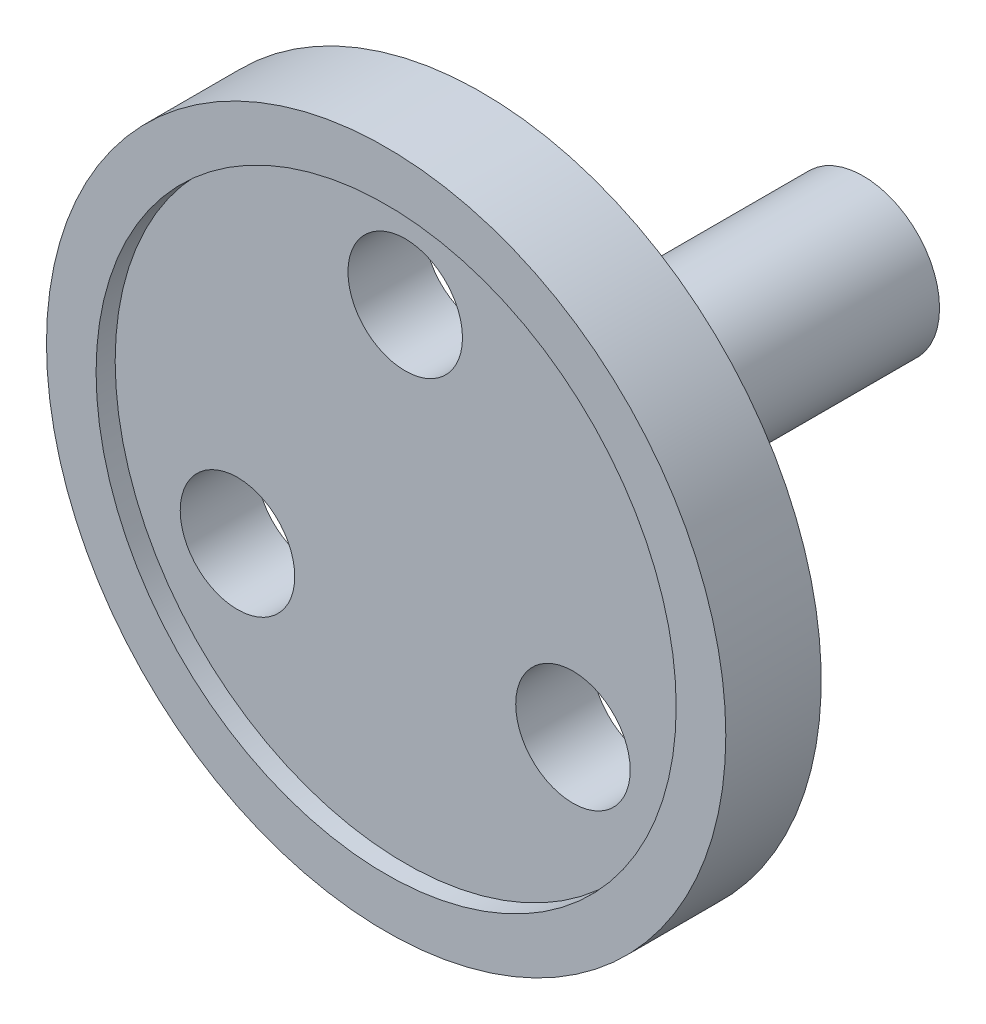
SolidWorks part; units mm, degrees
material "合金钢"
ref_plane "前视基准面" through (0, 0, 0) normal (0, 0, 1) x (1, 0, 0)
ref_plane "上视基准面" through (0, 0, 0) normal (0, 1, 0) x (1, 0, 0)
ref_plane "右视基准面" through (0, 0, 0) normal (1, 0, 0) x (0, 0, -1)
sketch "草图1" plane through (0, 0, 0) normal (0, 0, 1) x (1, 0, 0)
  circle A0 centre (0, 0) radius 8.9
  circle A1 centre (0, 0) radius 5.075 construction
  circle A2 centre (0, 5.075) radius 1.5
  circle A3 centre (4.3951, -2.5375) radius 1.5
  circle A4 centre (-4.3951, -2.5375) radius 1.5
  point P12 (0, 0)
  dimension "D1" = 3
extrude "凸台-拉伸1" add sketch "草图1" along normal blind 3.5
sketch "草图2" plane through (0, 0, 3.5) normal (0, 0, 1) x (1, 0, 0)
  circle A0 centre (0, 0) radius 7.6
extrude "切除-拉伸1" cut sketch "草图2" against normal blind 0.5
sketch "草图3" plane through (0, 0, 0) normal (0, 0, -1) x (-1, 0, 0)
  circle A0 centre (0, 0) radius 2
extrude "凸台-拉伸2" add sketch "草图3" along normal blind 13
ref_plane "基准面1" through (0, 0, -8.5) normal (0, 0, -1) x (-1, 0, 0)
sketch "草图8" plane through (0, 0, -8.5) normal (0, 0, -1) x (-1, 0, 0)
  circle A0 centre (0, 0) radius 4
extrude "凸台-拉伸4" add sketch "草图8" along normal blind 10
sketch "草图13" plane through (0, 0, -18.5) normal (0, 0, -1) x (-1, 0, 0)
  circle A1 centre (0, 0) radius 4
  circle A2 centre (0, 0) radius 4
  dimension "D1" = 0
extrude "切除-拉伸3" cut sketch "草图13" against normal blind 11.5
sketch "草图16" plane through (0, 0, 0) normal (0, 0, -1) x (-1, 0, 0)
  circle A0 centre (0, 0) radius 2 construction
  circle A1 centre (0, 0) radius 8.9
  circle A2 centre (0, 0) radius 8.9
  circle A3 centre (0, 0) radius 2
  dimension "D1" = 0
extrude "切除-拉伸5" cut sketch "草图16" against normal blind 1
sketch "草图17" plane through (0, 0, -7) normal (0, 0, -1) x (-1, 0, 0)
  circle A1 centre (0, 0) radius 2
  circle A2 centre (0, 0) radius 2
  dimension "D1" = 0
extrude "凸台-拉伸5" add sketch "草图17" along normal blind 2
